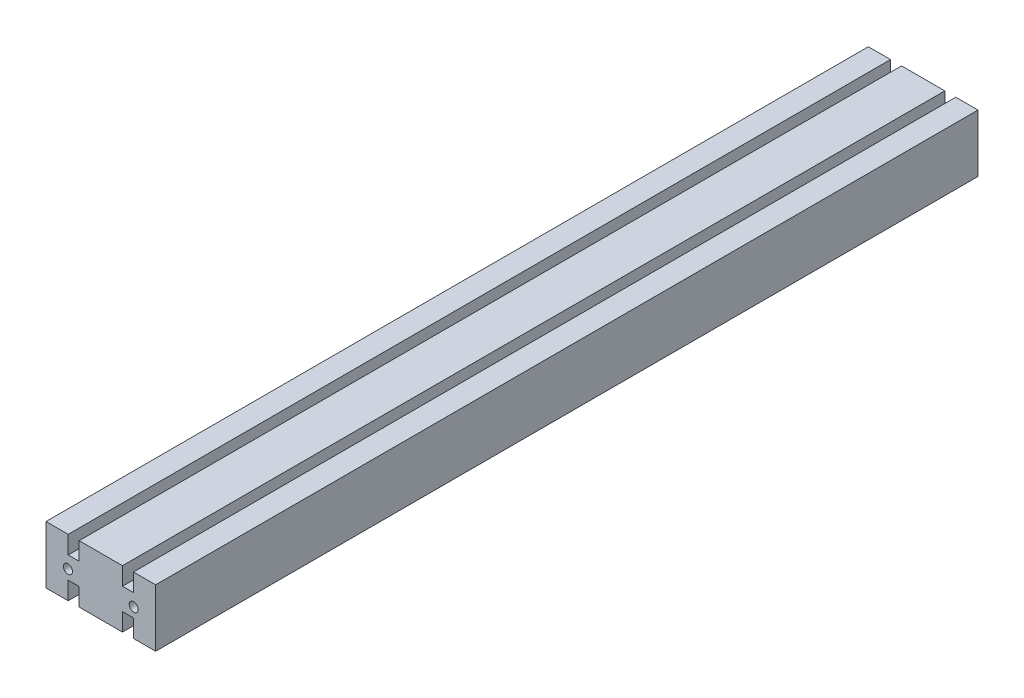
SolidWorks part; units mm, degrees
ref_plane "Front Plane" through (0, 0, 0) normal (0, 0, 1) x (1, 0, 0)
ref_plane "Top Plane" through (0, 0, 0) normal (0, 1, 0) x (1, 0, 0)
ref_plane "Right Plane" through (0, 0, 0) normal (1, 0, 0) x (0, 0, -1)
sketch "Sketch1" plane through (0, 0, 0) normal (0, 0, 1) x (1, 0, 0)
  line L1 (-20, -10.5) -> (20, -10.5)
  line L2 (-20, -10.5) -> (-20, 10.5)
  line L3 (-20, 10.5) -> (20, 10.5)
  line L4 (20, -10.5) -> (20, 10.5)
  line L5 (-20, -10.5) -> (20, 10.5) construction
  line L6 (-20, 10.5) -> (20, -10.5) construction
  point P0 (0, 0)
  dimension "D1" = 40
  dimension "D2" = 21
extrude "Boss-Extrude1" add sketch "Sketch1" along normal mid plane 300
sketch "Sketch2" plane through (0, 0, 0) normal (0, 0, 1) x (1, 0, 0)
  line L0 (0, 0) -> (0, 10.5) construction
  line L1 (7.9, 10.5) -> (11.9, 10.5)
  line L2 (7.9, 10.5) -> (7.9, 4)
  line L3 (7.9, 4) -> (11.9, 4)
  line L4 (11.9, 10.5) -> (11.9, 4)
  line L5 (20, 10.5) -> (-20, 10.5) construction
  line L6 (0, 0) -> (20, 0) construction
  line L7 (20, -10.5) -> (20, 10.5) construction
  line L8 (-7.9, 10.5) -> (-11.9, 10.5)
  line L9 (-11.9, 10.5) -> (-11.9, 4)
  line L10 (-7.9, 4) -> (-11.9, 4)
  line L11 (-7.9, 10.5) -> (-7.9, 4)
  line L12 (7.9, -10.5) -> (11.9, -10.5)
  line L13 (11.9, -10.5) -> (11.9, -4)
  line L14 (7.9, -10.5) -> (7.9, -4)
  line L15 (7.9, -4) -> (11.9, -4)
  line L16 (-7.9, -4) -> (-11.9, -4)
  line L17 (-7.9, -10.5) -> (-11.9, -10.5)
  line L18 (-7.9, -10.5) -> (-7.9, -4)
  line L19 (-11.9, -10.5) -> (-11.9, -4)
  dimension "D1" = 4
  dimension "D2" = 15.8
  dimension "D3" = 6.5
extrude "Cut-Extrude1" cut sketch "Sketch2" against normal through all both and the other way through all
sketch "Sketch3" plane through (0, 0, 0) normal (0, 0, 1) x (1, 0, 0)
  line L0 (-12, -0.5) -> (12, -0.5) construction
  line L1 (-7.9, -10.5) -> (7.9, -10.5) construction
  line L2 (0, 0) -> (0, -0.5) construction
  dimension "D1" = 24
  dimension "D2" = 10
hole_wizard "M4x0.7 Tapped Hole1" positions "Sketch4" profile "Sketch5" tap size "M4x0.7" standard "ANSI Metric"
sketch "Sketch4" plane through (0, 0, 150) normal (0, 0, 1) x (1, 0, 0)
  point P0 (-12, -0.5)
  point P3 (12, -0.5)
sketch "Sketch5" plane through (-12, -0.5, 150) normal (1, 0, 0) x (0, -1, 0)
  line L0 (0, 0) -> (0, 11.0914)
  line L1 (0, 11.0914) -> (1.65, 10.1)
  line L2 (1.65, 10.1) -> (1.65, 0)
  line L5 (1.65, 0) -> (0, 0)
  line L10 (0, 11.0914) -> (-1.65, 10.1) construction
  line L11 (0, -6.35) -> (0, 107.95) construction
  dimension "Tap Drill Dia." = 3.3
  dimension "Tap Drill Depth" = 10.1
  dimension "Drill Angle" = 118
cosmetic thread "Hole Thread1" parameters "D1"=8, "D2"=4
cosmetic thread "Hole Thread2" parameters "D1"=8, "D2"=4
hole_wizard "M4x0.7 Tapped Hole2" positions "Sketch6" profile "Sketch7" tap size "M4x0.7" standard "ANSI Metric"
sketch "Sketch6" plane through (0, 0, -150) normal (0, 0, -1) x (-1, 0, 0)
  point P0 (-12, -0.5)
  point P3 (12, -0.5)
sketch "Sketch7" plane through (12, -0.5, -150) normal (1, 0, 0) x (0, 1, 0)
  line L0 (0, 0) -> (0, 11.0914)
  line L1 (0, 11.0914) -> (1.65, 10.1)
  line L2 (1.65, 10.1) -> (1.65, 0)
  line L5 (1.65, 0) -> (0, 0)
  line L10 (0, 11.0914) -> (-1.65, 10.1) construction
  line L11 (0, -6.35) -> (0, 107.95) construction
  dimension "Tap Drill Dia." = 3.3
  dimension "Tap Drill Depth" = 10.1
  dimension "Drill Angle" = 118
cosmetic thread "Hole Thread3" parameters "D1"=8, "D2"=4
cosmetic thread "Hole Thread4" parameters "D1"=8, "D2"=4
